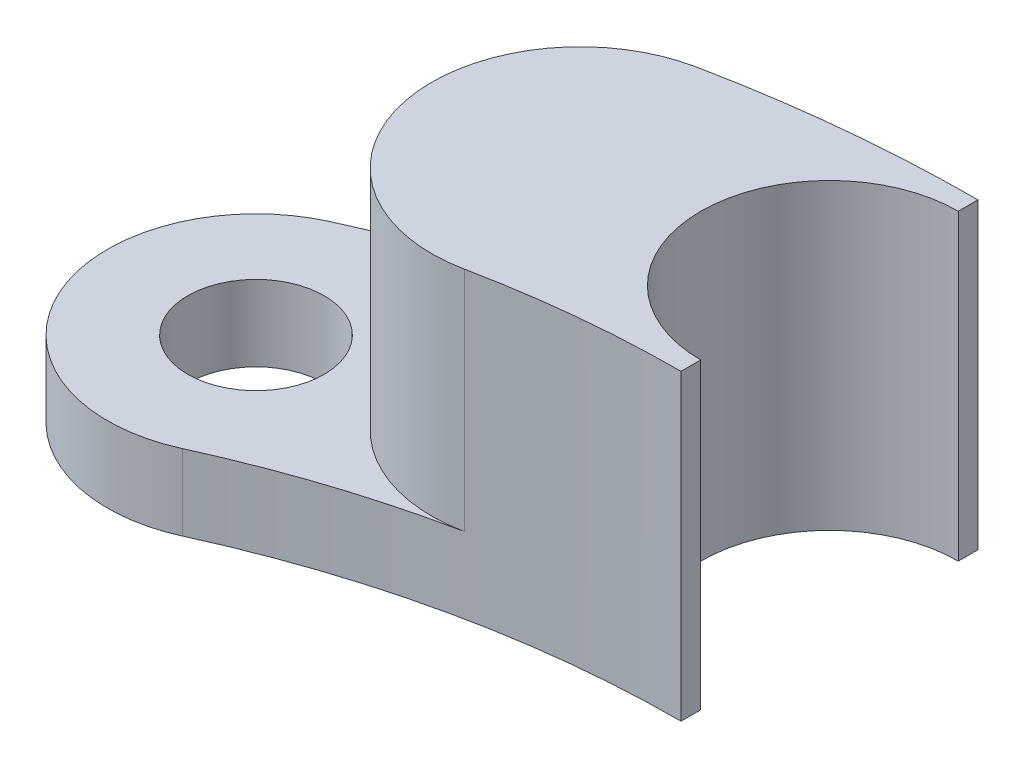
SolidWorks part; units mm, degrees
material "ﾎﾟﾘｴｽﾃﾙ樹脂"
ref_plane "正面" through (0, 0, 0) normal (0, 0, 1) x (1, 0, 0)
ref_plane "平面" through (0, 0, 0) normal (0, 1, 0) x (1, 0, 0)
ref_plane "右側面" through (0, 0, 0) normal (1, 0, 0) x (0, 0, -1)
sketch "ｽｹｯﾁ1" plane through (0, 0, 0) normal (0, 1, 0) x (1, 0, 0)
  line L0 (0, 0) -> (0, 42.4)
  line L1 (0, 0) -> (8.4532, 41.5488)
  line L2 (0, 0) -> (17.583, 38.5824) construction
  circle A0 centre (0, 0) radius 32.4 construction
  circle A1 centre (0, 0) radius 42.6 construction
  circle A2 centre (0, 0) radius 42.4
  circle A3 centre (0, 0) radius 32.6
  circle A4 centre (15.551, 34.1235) radius 2.25
  circle A5 centre (0, 0) radius 37.5 construction
  circle A6 centre (0, 37.5) radius 4.25
  circle A7 centre (15.551, 34.1235) radius 4.9
  circle A8 centre (-15.551, 34.1235) radius 2.25
  circle A9 centre (-15.551, 34.1235) radius 4.9
  dimension "D1" = 85.2
  dimension "D2" = 64.8
  dimension "D3" = 84.8
  dimension "D4" = 65.2
  dimension "D6" = 4.5
  dimension "D8" = 75
  dimension "D9" = 8.5
  dimension "D5" = 11.5
  dimension "D7" = 13
extrude "ﾎﾞｽ - 押し出し1" add sketch "ｽｹｯﾁ1" along normal blind 10 contours A2 A9 A3 L0 A6 | A9 A8
sketch "ｽｹｯﾁ2" plane through (0, 10, 0) normal (0, 1, 0) x (1, 0, 0)
  line L0 (0, 0) -> (8.4532, 41.5488) construction
  line L1 (0, 0) -> (0, 50000) construction
  circle A1 centre (7.4763, 36.7472) radius 4.9
  arc A2 (-17.583, 38.5824) -> (-12.2699, 37.7628) centre (-15.551, 34.1235) cw construction
  circle A3 centre (15.551, 34.1235) radius 4.9
  circle A4 centre (0, 0) radius 32.6
  circle A5 centre (0, 0) radius 42.4
  circle A6 centre (-7.4763, 36.7472) radius 4.9
  arc A7 (-12.2699, 37.7628) -> (-10.7574, 33.1079) centre (-15.551, 34.1235) cw construction
  arc A8 (-10.7574, 33.1079) -> (-13.519, 29.6647) centre (-15.551, 34.1235) cw construction
  arc A9 (-13.519, 29.6647) -> (-17.583, 38.5824) centre (-15.551, 34.1235) cw
  dimension "D2" = 9.8
  dimension "D3" = 84.8
  dimension "D4" = 65.2
  dimension "D1" = 11.5
extrude "ｶｯﾄ - 押し出し1" cut sketch "ｽｹｯﾁ2" against normal blind 7.5 contours A7 A6 | A5
